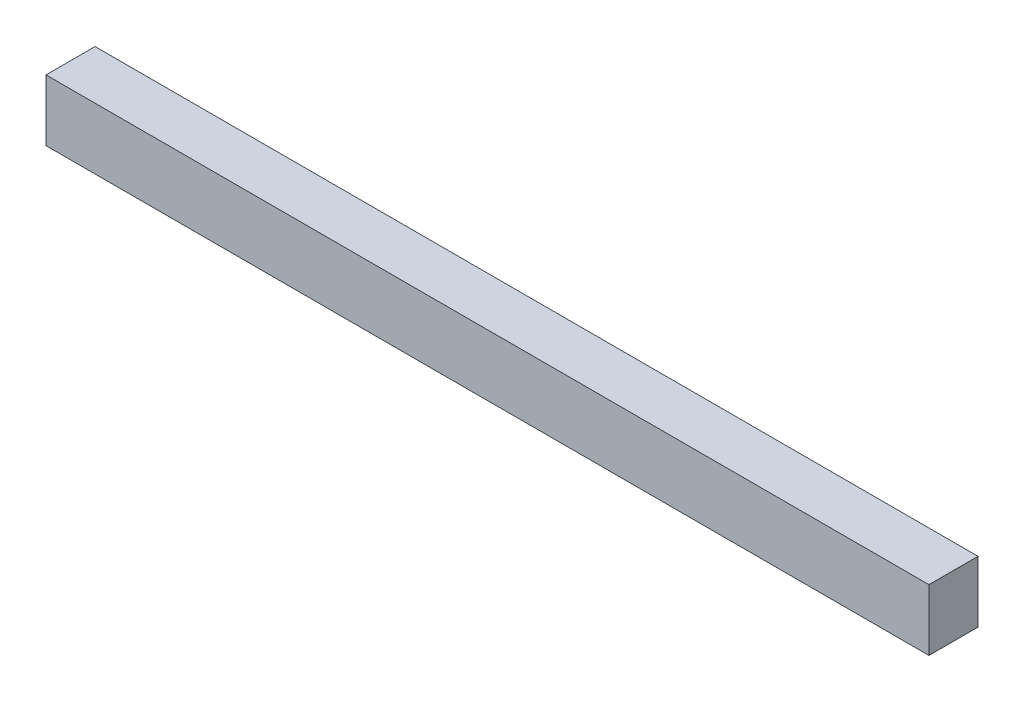
SolidWorks part; units mm, degrees
ref_plane "Front Plane" through (0, 0, 0) normal (0, 0, 1) x (1, 0, 0)
ref_plane "Top Plane" through (0, 0, 0) normal (0, 1, 0) x (1, 0, 0)
ref_plane "Right Plane" through (0, 0, 0) normal (1, 0, 0) x (0, 0, -1)
sketch "Sketch1" plane through (0, 0, 0) normal (1, 0, 0) x (0, 0, -1)
  line L1 (10, 12.5) -> (-10, 12.5)
  line L2 (10, 12.5) -> (10, -12.5)
  line L3 (10, -12.5) -> (-10, -12.5)
  line L4 (-10, 12.5) -> (-10, -12.5)
  line L5 (10, 12.5) -> (-10, -12.5) construction
  line L6 (10, -12.5) -> (-10, 12.5) construction
  point P0 (0, 0)
  dimension "D1" = 25
  dimension "D2" = 20
extrude "Boss-Extrude1" add sketch "Sketch1" along normal blind 360
